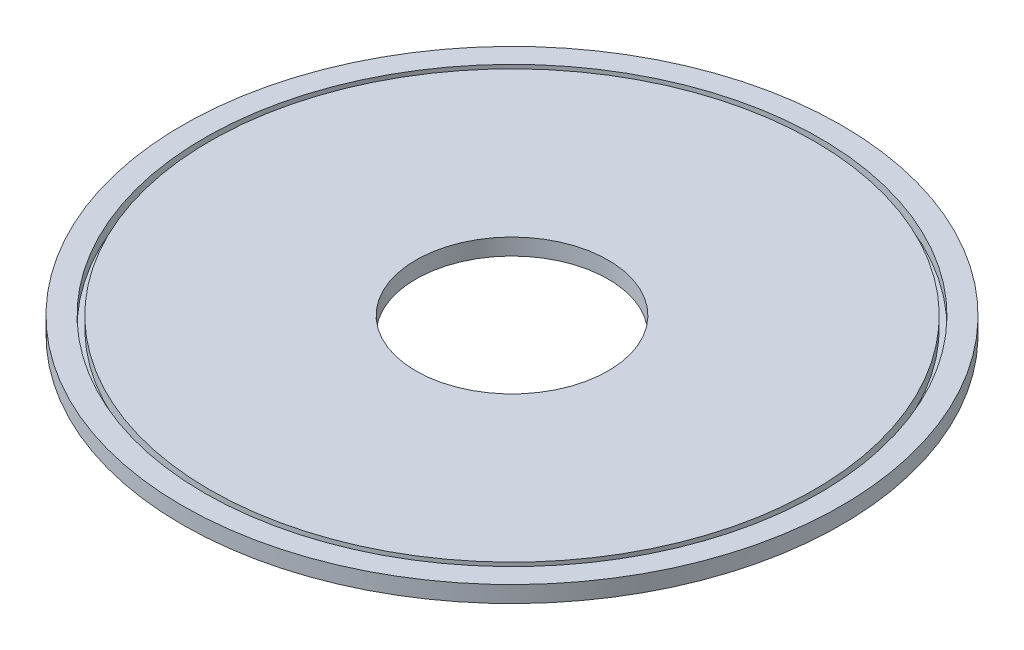
SolidWorks part; units mm, degrees
ref_plane "Front Plane" through (0, 0, 0) normal (0, 0, 1) x (1, 0, 0)
ref_plane "Top Plane" through (0, 0, 0) normal (0, 1, 0) x (1, 0, 0)
ref_plane "Right Plane" through (0, 0, 0) normal (1, 0, 0) x (0, 0, -1)
sketch "Sketch1" plane through (0, 0, 0) normal (0, 1, 0) x (1, 0, 0)
  circle A0 centre (0, 0) radius 300
  point P0 (0, 0)
  dimension "D1" = 600
extrude "plate" add sketch "Sketch1" along normal blind 15
sketch "Sketch2" plane through (0, 15, 0) normal (0, 1, 0) x (1, 0, 0)
  circle A0 centre (0, 0) radius 87.5
  dimension "D1" = 175
extrude "bearing-hole" cut sketch "Sketch2" against normal through all
sketch "Sketch4" plane through (0, 15, 0) normal (0, 1, 0) x (1, 0, 0)
  circle A0 centre (0, 0) radius 280
  circle A1 centre (0, 0) radius 275
  point P0 (0, 0)
  point P6 (0, 0)
  dimension "D1" = 560
  dimension "D2" = 550
extrude "Cut-Extrude3" cut sketch "Sketch4" against normal blind 10
